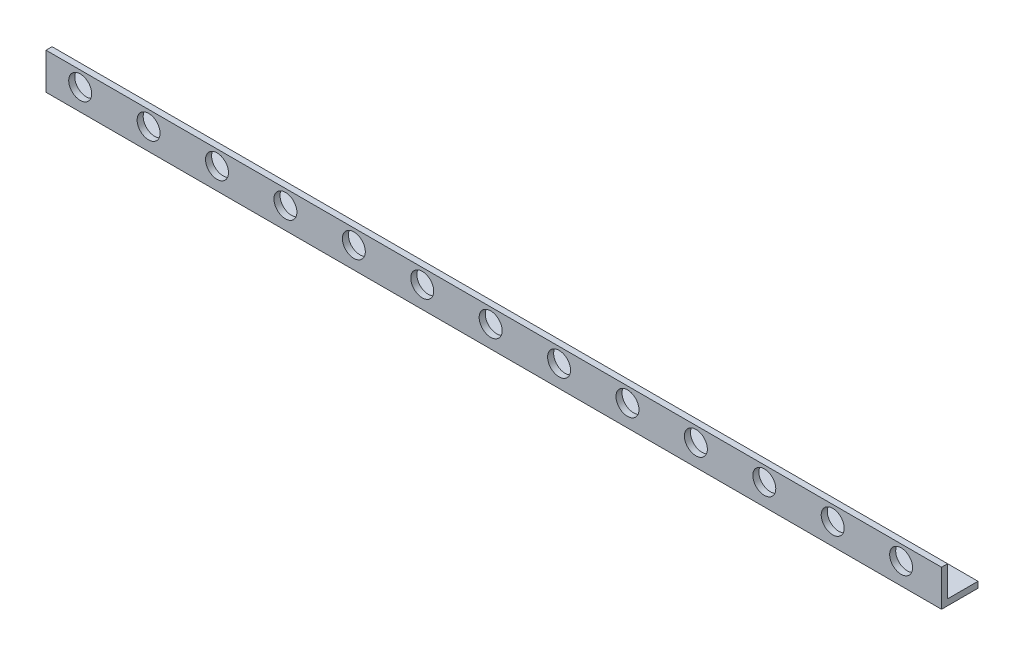
SolidWorks part; units mm, degrees
ref_plane "Front Plane" through (0, 0, 0) normal (0, 0, 1) x (1, 0, 0)
ref_plane "Top Plane" through (0, 0, 0) normal (0, 1, 0) x (1, 0, 0)
ref_plane "Right Plane" through (0, 0, 0) normal (1, 0, 0) x (0, 0, -1)
sketch "Sketch1" plane through (0, 0, 0) normal (1, 0, 0) x (0, 0, -1)
  line L0 (0, 0) -> (0, 19.05)
  line L1 (0, 19.05) -> (3.175, 19.05)
  line L2 (3.175, 19.05) -> (3.175, 3.175)
  line L3 (3.175, 3.175) -> (19.05, 3.175)
  line L4 (19.05, 3.175) -> (19.05, 0)
  line L5 (19.05, 0) -> (0, 0)
extrude "Boss-Extrude1" add sketch "Sketch1" against normal blind 468
sketch "Sketch2" plane through (0, 0, 0) normal (0, 0, 1) x (1, 0, 0)
  circle A0 centre (-450.13, 11.2735) radius 6
  circle A1 centre (-414.38, 11.2735) radius 6
  circle A2 centre (-378.63, 11.2735) radius 6
  circle A3 centre (-342.88, 11.2735) radius 6
  circle A4 centre (-307.13, 11.2735) radius 6
  circle A5 centre (-271.38, 11.2735) radius 6
  circle A6 centre (-235.63, 11.2735) radius 6
  circle A7 centre (-199.88, 11.2735) radius 6
  circle A8 centre (-164.13, 11.2735) radius 6
  circle A9 centre (-128.38, 11.2735) radius 6
  circle A10 centre (-92.63, 11.2735) radius 6
  circle A11 centre (-56.88, 11.2735) radius 6
  circle A12 centre (-21.13, 11.2735) radius 6
extrude "Cut-Extrude1" cut sketch "Sketch2" against normal blind 3.175
